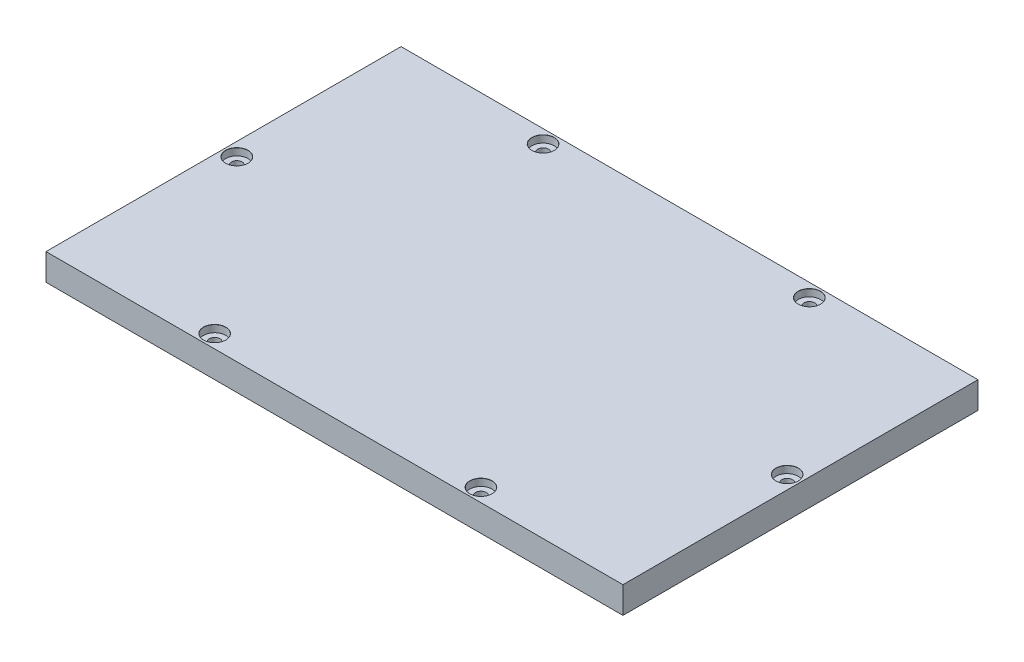
SolidWorks part; units mm, degrees
ref_plane "Ebene vorne" through (0, 0, 0) normal (0, 0, 1) x (1, 0, 0)
ref_plane "Ebene oben" through (0, 0, 0) normal (0, 1, 0) x (1, 0, 0)
ref_plane "Ebene rechts" through (0, 0, 0) normal (1, 0, 0) x (0, 0, -1)
sketch "Skizze1" plane through (0, 0, 0) normal (0, 1, 0) x (1, 0, 0)
  line L1 (0, 0) -> (130, 0)
  line L2 (0, 0) -> (0, 80)
  line L3 (0, 80) -> (130, 80)
  line L4 (130, 0) -> (130, 80)
  dimension "D1" = 80
  dimension "D2" = 130
extrude "Aufsatz-Linear austragen1" add sketch "Skizze1" along normal blind 6
hole_wizard "Ø2.4 (2.4) Durchmesser Bohrung1" positions "Skizze2" profile "Skizze3" hole size "Ø2.4" standard "DIN"
sketch "Skizze2" plane through (0, 6, 0) normal (0, 1, 0) x (1, 0, 0)
  line L0 (130, 80) -> (0, 80) construction
  line L1 (130, 0) -> (130, 80) construction
  line L2 (0, -3.3) -> (0, 3.3) construction
  line L3 (-3.3, 0) -> (3.3, 0) construction
  point P0 (35, 77)
  point P2 (95, 77)
  point P4 (127, 40)
  point P6 (95, 3)
  point P8 (35, 3)
  point P10 (3, 40)
  point P21 (133.0887, 32.8034)
  dimension "D1" = 3
  dimension "D2" = 3
  dimension "D3" = 3
  dimension "D4" = 3
  dimension "D5" = 3
  dimension "D6" = 3
  dimension "D7" = 35
  dimension "D8" = 35
  dimension "D9" = 35
  dimension "D10" = 35
  dimension "D11" = 40
  dimension "D12" = 40
sketch "Skizze3" plane through (35, 6, -77) normal (1, 0, 0) x (0, 0, 1)
  line L0 (0, 0) -> (0, 10.721)
  line L1 (0, 10.721) -> (1.2, 10)
  line L2 (1.2, 10) -> (1.2, 0.025)
  line L3 (1.2, 0.025) -> (1.225, 0)
  line L5 (1.225, 0) -> (0, 0)
  line L6 (-1.2, 0.025) -> (-1.225, 0) construction
  line L10 (0, 10.721) -> (-1.2, 10) construction
  line L11 (0, -6.35) -> (0, 107.95) construction
  dimension "Bohrerdurchmesser" = 2.4
  dimension "Bohrungstiefe" = 10
  dimension "Senkdurchmesser2 (Oben)" = 2.45
  dimension "Senkwinkel2 (Oben)" = 90
  dimension "Spitzenwinkel" = 118
hole_wizard "Stirnsenkung für M2 Flachkopfschraube mit Schlitz1" positions "Skizze6" profile "Skizze7" counterbore size "M2" standard "DIN"
sketch "Skizze6" plane through (0, 6, 0) normal (0, 1, 0) x (1, 0, 0)
  point P0 (95, 3)
  point P3 (127, 40)
  point P6 (95, 77)
  point P9 (35, 77)
  point P12 (3, 40)
  point P15 (35, 3)
sketch "Skizze7" plane through (95, 6, -3) normal (1, 0, 0) x (0, 0, 1)
  line L0 (0, 0) -> (0, 2.721)
  line L1 (0, 2.721) -> (1.2, 2)
  line L2 (1.2, 2) -> (1.2, 1.6)
  line L3 (1.2, 1.6) -> (2.5, 1.6)
  line L5 (2.5, 1.6) -> (2.5, 0.025)
  line L6 (2.5, 0.025) -> (2.525, 0)
  line L7 (2.525, 0) -> (0, 0)
  line L8 (-2.5, 0.025) -> (-2.525, 0) construction
  line L10 (0, 2.721) -> (-1.2, 2) construction
  line L11 (0, -6.35) -> (0, 107.95) construction
  dimension "Bohrerdurchmesser" = 2.4
  dimension "Bohrungstiefe" = 2
  dimension "Senkdurchmesser2" = 5
  dimension "Senktiefe2" = 1.6
  dimension "Senkdurchmesser4 (Oben)" = 5.05
  dimension "Senkwinkel2 (Oben)" = 90
  dimension "Spitzenwinkel" = 118
